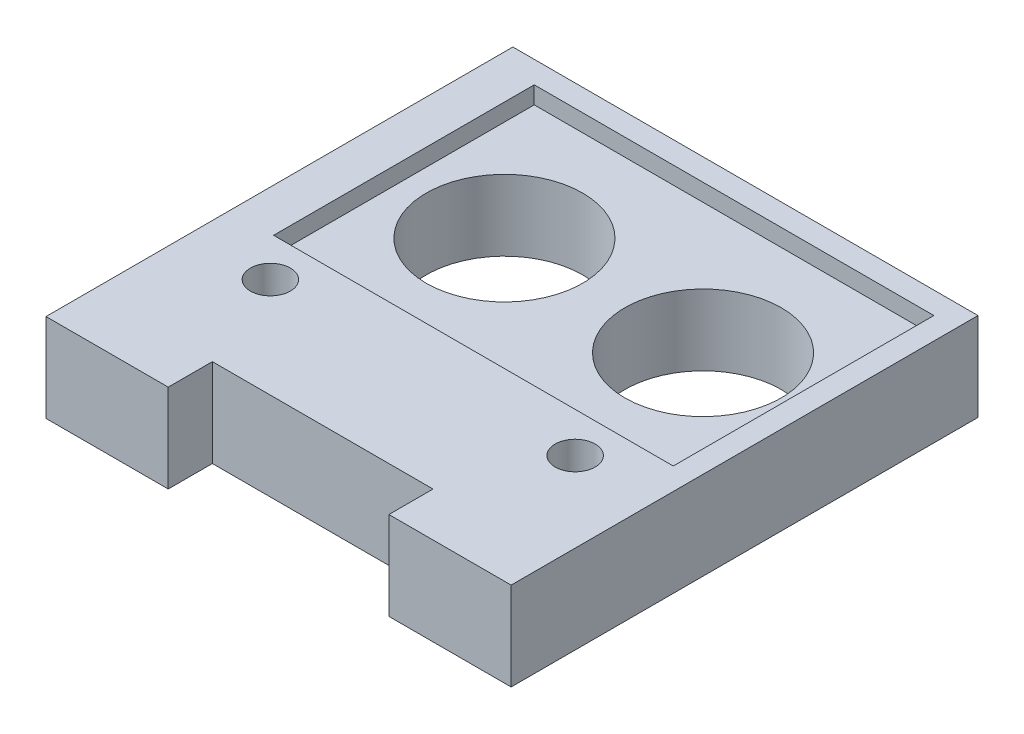
SolidWorks part; units mm, degrees
ref_plane "Front Plane" through (0, 0, 0) normal (0, 0, 1) x (1, 0, 0)
ref_plane "Top Plane" through (0, 0, 0) normal (0, 1, 0) x (1, 0, 0)
ref_plane "Right Plane" through (0, 0, 0) normal (1, 0, 0) x (0, 0, -1)
sketch "Sketch1" plane through (0, 0, 0) normal (0, 1, 0) x (1, 0, 0)
  line L0 (-9.385, -9.8) -> (8.155, -9.8) construction
  line L1 (-11.5, -7.5) -> (11.5, -7.5) construction
  line L2 (-11.5, -7.5) -> (-11.5, 7.5) construction
  line L3 (-11.5, 7.5) -> (11.5, 7.5) construction
  line L4 (11.5, -7.5) -> (11.5, 7.5) construction
  line L5 (-14, 8.77) -> (12.77, 8.77)
  line L6 (-14, 8.77) -> (-14, -18.1)
  line L7 (-14, -18.1) -> (-6.965, -18.1)
  line L8 (12.77, 8.77) -> (12.77, -18.1)
  line L9 (-0.615, -15.56) -> (-0.615, -9.8) construction
  line L10 (-5.715, 0) -> (5.715, 0) construction
  line L11 (-11.5, 7.5) -> (11.5, -7.5) construction
  line L12 (5.735, -18.1) -> (12.77, -18.1)
  line L14 (-6.965, -18.1) -> (-6.965, -15.56)
  line L15 (-6.965, -15.56) -> (5.735, -15.56)
  line L16 (5.735, -18.1) -> (5.735, -15.56)
  circle A0 centre (-5.715, 0) radius 4.5
  circle A1 centre (5.715, 0) radius 4.5
  circle A3 centre (-9.385, -9.8) radius 1.15
  circle A4 centre (8.155, -9.8) radius 1.15
  point P21 (0, 0)
  point P24 (5.0512, -10.6)
  point P25 (0, 0)
  point P26 (10.885, -8.06)
  point P27 (0, 0)
  point P28 (-6.3129, 4.1934)
  point P29 (0, 0)
  dimension "D3" = 9
  dimension "D4" = 11.43
  dimension "D5" = 25.6
  dimension "D6" = 2.5
  dimension "D17" = 17.54
  dimension "D18" = 2.3
  dimension "D19" = 2.3
  dimension "D1" = 23
  dimension "D2" = 15
  dimension "D7" = 1.27
  dimension "D8" = 1.27
  dimension "D9" = 8.3
  dimension "D10" = 12.7
  dimension "D11" = 2.54
extrude "Boss-Extrude1" add sketch "Sketch1" along normal blind 5.08
sketch "Sketch4" plane through (0, 5.08, 0) normal (0, 1, 0) x (1, 0, 0)
  line L1 (-11.5, 7.5) -> (11.5, 7.5)
  line L2 (-11.5, 7.5) -> (-11.5, -7.5)
  line L3 (-11.5, -7.5) -> (11.5, -7.5)
  line L4 (11.5, 7.5) -> (11.5, -7.5)
  line L5 (-11.5, 7.5) -> (11.5, -7.5) construction
  line L6 (-11.5, -7.5) -> (11.5, 7.5) construction
  point P0 (0, 0)
  point P6 (-11.5, 7.5)
extrude "Cut-Extrude1" cut sketch "Sketch4" against normal blind 1
